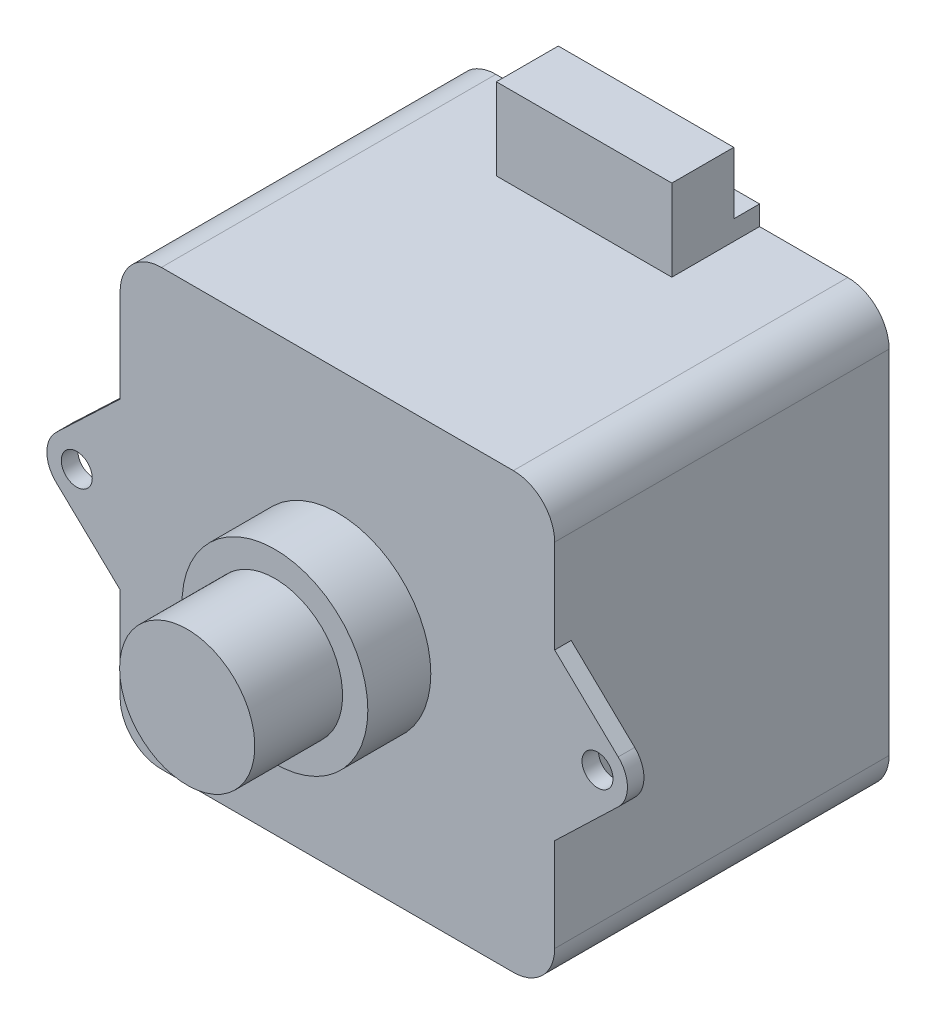
SolidWorks part; units mm, degrees
material "1023 Carbon Steel Sheet (SS)"
ref_plane "Front Plane" through (0, 0, 0) normal (0, 0, 1) x (1, 0, 0)
ref_plane "Top Plane" through (0, 0, 0) normal (0, 1, 0) x (1, 0, 0)
ref_plane "Right Plane" through (0, 0, 0) normal (1, 0, 0) x (0, 0, -1)
sketch "Sketch1" plane through (0, 0, 0) normal (0, 0, 1) x (1, 0, 0)
  line L1 (0, 0) -> (-42.1, 0)
  line L2 (0, 0) -> (0, 42.1)
  line L3 (0, 42.1) -> (-42.1, 42.1)
  line L4 (-42.1, 0) -> (-42.1, 42.1)
  dimension "D1" = 42.1
  dimension "D2" = 42.1
extrude "Boss-Extrude1" add sketch "Sketch1" along normal blind 32.4
sketch "Sketch2" plane through (0, 42.1, 0) normal (0, 1, 0) x (1, 0, 0)
  line L0 (0, 0) -> (-42.1, 0) construction
  line L1 (-29.55, 0) -> (-12.55, 0)
  line L2 (-29.55, 0) -> (-29.55, -8.5)
  line L3 (-29.55, -8.5) -> (-12.55, -8.5)
  line L4 (-12.55, 0) -> (-12.55, -8.5)
  line L5 (-42.1, -32.4) -> (-42.1, 0) construction
  dimension "D1" = 17
  dimension "D2" = 12.55
  dimension "D3" = 8.5
extrude "Boss-Extrude2" add sketch "Sketch2" along normal blind 7.9
sketch "Sketch3" plane through (0, 0, 0) normal (1, 0, 0) x (0, 0, -1)
  line L0 (-32.4, 0) -> (-32.4, 42.1) construction
  line L2 (-32.4, 21.05) -> (-32.4, 29.05)
  line L3 (-32.4, 29.05) -> (-30.8, 29.05)
  line L4 (-30.8, 21.05) -> (-30.8, 29.05)
  line L7 (-32.4, 21.05) -> (-32.4, 13.05)
  line L8 (-32.4, 13.05) -> (-30.8, 13.05)
  line L9 (-30.8, 21.05) -> (-30.8, 13.05)
  dimension "D1" = 8
  dimension "D2" = 8
  dimension "D3" = 1.6
extrude "Boss-Extrude3" add sketch "Sketch3" along normal blind 7.15
sketch "Sketch4" plane through (-42.1, 0, 0) normal (-1, 0, 0) x (0, 0, 1)
  line L0 (32.4, 42.1) -> (32.4, 0) construction
  line L2 (32.4, 21.05) -> (32.4, 29.05)
  line L3 (32.4, 29.05) -> (30.8, 29.05)
  line L4 (30.8, 21.05) -> (30.8, 29.05)
  line L7 (30.8, 21.05) -> (30.8, 13.05)
  line L8 (30.8, 13.05) -> (32.4, 13.05)
  line L9 (32.4, 21.05) -> (32.4, 13.05)
  dimension "D1" = 8
  dimension "D2" = 8
  dimension "D3" = 1.6
extrude "Boss-Extrude4" add sketch "Sketch4" along normal blind 7.2
sketch "Sketch6" plane through (0, 0, 32.4) normal (0, 0, 1) x (1, 0, 0)
  line L0 (-49.3, 13.05) -> (-49.3, 29.05) construction
  line L1 (7.15, 29.05) -> (7.15, 13.05) construction
  circle A0 centre (-46.3, 21.0607) radius 1.5
  circle A1 centre (4.15, 21.0607) radius 1.5
  dimension "D1" = 3
  dimension "D2" = 3
  dimension "D3" = 3
  dimension "D4" = 3
extrude "Cut-Extrude1" cut sketch "Sketch6" against normal blind 7.2
sketch "Sketch7" plane through (0, 0, 32.4) normal (0, 0, 1) x (1, 0, 0)
  line L0 (-42.1, 29.05) -> (-48.2972, 23.1633)
  line L1 (-42.1, 13.05) -> (-48.3011, 18.9617)
  line L2 (0, 29.05) -> (6.1557, 23.1552)
  line L3 (0, 13.05) -> (6.1595, 18.9698)
  line L4 (-42.1, 29.05) -> (-49.3, 29.05)
  line L5 (-49.3, 29.05) -> (-49.3, 13.05)
  line L6 (-49.3, 13.05) -> (-42.1, 13.05)
  line L7 (0, 29.05) -> (7.15, 29.05)
  line L8 (7.15, 29.05) -> (7.15, 13.05)
  line L9 (7.15, 13.05) -> (0, 13.05)
  arc A0 (-48.2972, 23.1633) -> (-48.3011, 18.9617) centre (-46.3, 21.0607) ccw
  arc A1 (6.1595, 18.9698) -> (6.1557, 23.1552) centre (4.15, 21.0607) ccw
  dimension "D1" = 2.9
extrude "Cut-Extrude2" cut sketch "Sketch7" against normal blind 7.2
sketch "Sketch9" plane through (0, 0, 32.4) normal (0, 0, 1) x (1, 0, 0)
  line L0 (0, 42.1) -> (-42.1, 42.1) construction
  line L2 (-42.1, 42.1) -> (-42.1, 29.05) construction
  circle A0 centre (-21, 21.05) radius 6.55
  dimension "D1" = 21.05
  dimension "D2" = 21.1
extrude "Boss-Extrude5" add sketch "Sketch9" along normal blind 14.6
sketch "Sketch11" plane through (0, 0, 32.4) normal (0, 0, 1) x (1, 0, 0)
  circle A0 centre (-21, 21.05) radius 9
extrude "Boss-Extrude6" add sketch "Sketch11" along normal blind 6.1
sketch "Sketch12" plane through (0, 50, 0) normal (0, 1, 0) x (1, 0, 0)
  line L0 (-12.55, 0) -> (-29.55, 0) construction
  line L1 (-12.55, 0) -> (-29.55, 0)
  line L2 (-12.55, 0) -> (-12.55, -2.5)
  line L3 (-12.55, -2.5) -> (-29.55, -2.5)
  line L4 (-29.55, 0) -> (-29.55, -2.5)
  line L5 (-12.55, -8.5) -> (-12.55, 0) construction
  line L6 (-29.55, 0) -> (-29.55, -8.5) construction
  line L7 (-29.55, -8.5) -> (-12.55, -8.5) construction
  dimension "D1" = 6
extrude "Cut-Extrude3" cut sketch "Sketch12" against normal blind 6
sketch "Sketch13" plane through (0, 0, 0) normal (0, 0, -1) x (-1, 0, 0)
  line L0 (0, 0) -> (0, 42.1) construction
  line L1 (0, 42.1) -> (12.55, 42.1) construction
  line L2 (29.55, 42.1) -> (42.1, 42.1) construction
  line L3 (42.1, 42.1) -> (42.1, 0) construction
  line L4 (42.1, 0) -> (0, 0) construction
  line L5 (0, 0) -> (0, 4)
  line L6 (4, 0) -> (0, 0)
  line L7 (38.1, 0) -> (42.1, 0)
  line L8 (42.1, 0) -> (42.1, 4)
  line L9 (38.1, 42.1) -> (42.1, 42.1)
  line L10 (42.1, 42.1) -> (42.1, 38.1)
  line L11 (4, 42.1) -> (0, 42.1)
  line L12 (0, 42.1) -> (0, 38.1)
  arc A0 (4, 42.1) -> (0, 38.1) centre (4, 38.1) ccw
  arc A1 (42.1, 38.1) -> (38.1, 42.1) centre (38.1, 38.1) ccw
  arc A2 (38.1, 0) -> (42.1, 4) centre (38.1, 4) ccw
  arc A3 (0, 4) -> (4, 0) centre (4, 4) ccw
  dimension "D8" = 8
  dimension "D9" = 8
  dimension "D10" = 8
  dimension "D11" = 8
  dimension "D1" = 4
  dimension "D2" = 4
  dimension "D3" = 4
  dimension "D4" = 4
  dimension "D5" = 4
  dimension "D6" = 4
  dimension "D7" = 4
  dimension "D12" = 4
extrude "Cut-Extrude4" cut sketch "Sketch13" against normal blind 40
